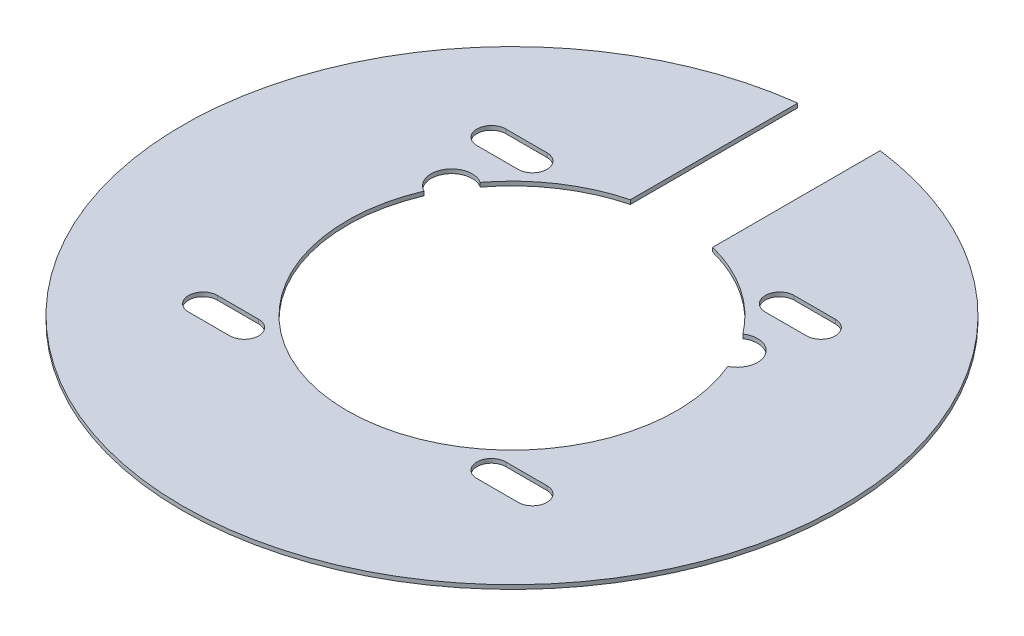
SolidWorks part; units mm, degrees
ref_plane "前视基准面" through (0, 0, 0) normal (0, 0, 1) x (1, 0, 0)
ref_plane "上视基准面" through (0, 0, 0) normal (0, 1, 0) x (1, 0, 0)
ref_plane "右视基准面" through (0, 0, 0) normal (1, 0, 0) x (0, 0, -1)
sketch "草图1" plane through (0, 0, 0) normal (0, 1, 0) x (1, 0, 0)
  line L0 (0, 40) -> (0, 80) construction
  line L1 (-10, 79.3725) -> (-10, 38.7298)
  line L2 (10, 79.3725) -> (10, 38.7298)
  arc A0 (-10, 38.7298) -> (10, 38.7298) centre (0, 0) ccw
  arc A1 (-10, 79.3725) -> (10, 79.3725) centre (0, 0) ccw
  dimension "D1" = 80
  dimension "D2" = 160
  dimension "D3" = 20
extrude "凸台-拉伸1" add sketch "草图1" along normal blind 1
sketch "草图2" plane through (0, 1, 0) normal (0, 1, 0) x (1, 0, 0)
  line L0 (-40, 35) -> (-30, 35) construction
  line L1 (-40, 35) -> (40, 35) construction
  line L2 (-40, 35) -> (-40, -35) construction
  line L3 (-40, -35) -> (40, -35) construction
  line L4 (40, 35) -> (40, -35) construction
  line L5 (0, -35) -> (0, 35) construction
  line L6 (-40, 0) -> (40, 0) construction
  line L7 (30, -35) -> (-30, -35) construction
  line L8 (30, -35) -> (30, 35) construction
  line L9 (30, 35) -> (-30, 35) construction
  line L10 (-30, -35) -> (-30, 35) construction
  line L11 (0, 35) -> (0, -35) construction
  line L12 (30, 0) -> (-30, 0) construction
  line L13 (-40, 38.5) -> (-30, 38.5)
  line L14 (-40, 31.5) -> (-30, 31.5)
  line L15 (30, 35) -> (40, 35) construction
  line L16 (30, 38.5) -> (40, 38.5)
  line L17 (30, 31.5) -> (40, 31.5)
  line L18 (30, -35) -> (40, -35) construction
  line L19 (30, -31.5) -> (40, -31.5)
  line L20 (30, -38.5) -> (40, -38.5)
  line L21 (-40, -35) -> (-30, -35) construction
  line L22 (-40, -31.5) -> (-30, -31.5)
  line L23 (-40, -38.5) -> (-30, -38.5)
  arc A0 (-40, 38.5) -> (-40, 31.5) centre (-40, 35) ccw
  arc A1 (-30, 31.5) -> (-30, 38.5) centre (-30, 35) ccw
  arc A2 (30, 38.5) -> (30, 31.5) centre (30, 35) ccw
  arc A3 (40, 31.5) -> (40, 38.5) centre (40, 35) ccw
  arc A4 (30, -31.5) -> (30, -38.5) centre (30, -35) ccw
  arc A5 (40, -38.5) -> (40, -31.5) centre (40, -35) ccw
  arc A6 (-40, -31.5) -> (-40, -38.5) centre (-40, -35) ccw
  arc A7 (-30, -38.5) -> (-30, -31.5) centre (-30, -35) ccw
  point P0 (0, 0)
  point P4 (-35, 35)
  point P5 (0, 0)
  point P19 (35, 35)
  point P29 (35, -35)
  point P36 (-35, -35)
  dimension "D3" = 2
  dimension "D5" = 3.5
  dimension "D1" = 70
  dimension "D2" = 80
  dimension "D9" = 60
  dimension "D4" = 2
extrude "切除-拉伸1" cut sketch "草图2" against normal blind 1
sketch "草图4" plane through (0, 1, 0) normal (0, 1, 0) x (1, 0, 0)
  line L0 (0, 0) -> (62.3088, 0) construction
  line L1 (0, 0) -> (34.641, 20) construction
  line L2 (0, 22.3361) -> (0, -17.9908) construction
  circle A0 centre (0, 0) radius 40 construction
  circle A1 centre (34.641, 20) radius 5
  circle A2 centre (-34.641, 20) radius 5
  dimension "D1" = 80
  dimension "D2" = 10
  dimension "D3" = 30
extrude "切除-拉伸2" cut sketch "草图4" against normal blind 1
